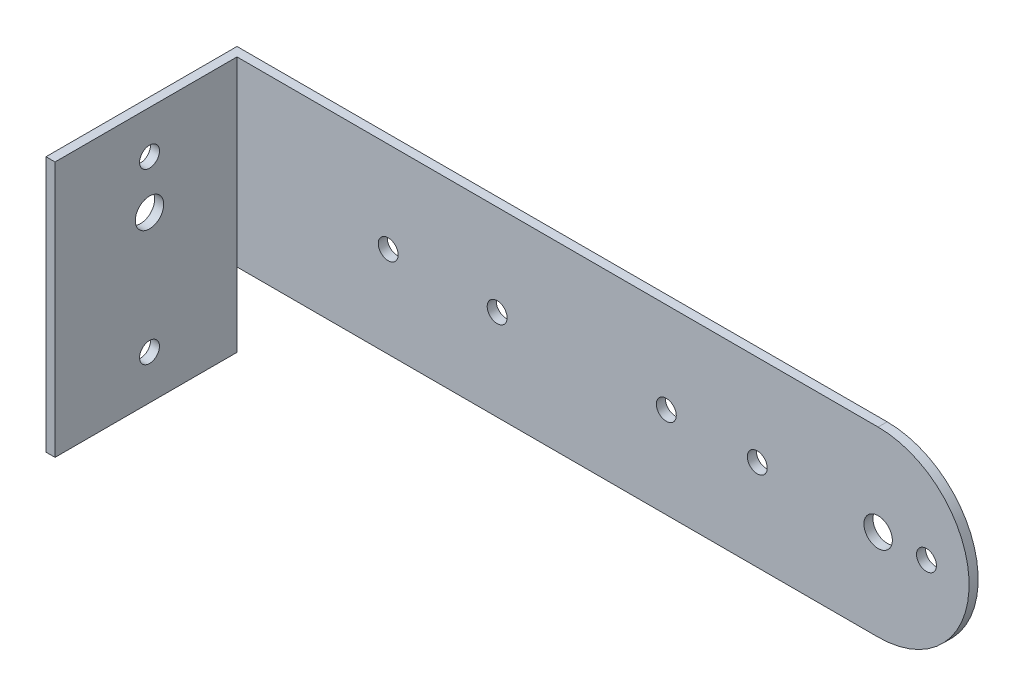
SolidWorks part; units mm, degrees
material "6061 Alloy"
ref_plane "Front Plane" through (0, 0, 0) normal (0, 0, 1) x (1, 0, 0)
ref_plane "Top Plane" through (0, 0, 0) normal (0, 1, 0) x (1, 0, 0)
ref_plane "Right Plane" through (0, 0, 0) normal (1, 0, 0) x (0, 0, -1)
sketch "Sketch1" plane through (0, 0, 0) normal (0, 0, 1) x (1, 0, 0)
  line L0 (0, 16) -> (-114.34, 16)
  line L1 (-114.34, 16) -> (-114.34, -16)
  line L2 (-114.34, -16) -> (0, -16)
  arc A0 (0, -16) -> (0, 16) centre (0, 0) ccw
  dimension "D1" = 16
  dimension "D2" = 114.34
extrude "Boss-Extrude1" add sketch "Sketch1" along normal blind 1.59
sketch "Sketch2" plane through (0, 0, 1.59) normal (0, 0, 1) x (1, 0, 0)
  line L1 (-114.34, 16) -> (-112.75, 16)
  line L2 (-114.34, 16) -> (-114.34, -29)
  line L3 (-114.34, -29) -> (-112.75, -29)
  line L4 (-112.75, 16) -> (-112.75, -29)
  point P5 (-112.75, -6.5)
  dimension "D1" = 45
  dimension "D2" = 1.59
extrude "Boss-Extrude2" add sketch "Sketch2" along normal blind 32
sketch "Sketch3" plane through (0, 0, 1.59) normal (0, 0, 1) x (1, 0, 0)
  line L0 (16, 0) -> (-148.456, 0) construction
  line L1 (-112.75, -16) -> (-112.75, 16) construction
  arc A0 (0, -16) -> (0, 16) centre (0, 0) ccw construction
  circle A1 centre (0, 0) radius 2.5
  circle A2 centre (8.5, 0) radius 1.75
  circle A3 centre (-21.25, 0) radius 1.75
  circle A4 centre (-37.25, 0) radius 1.75
  circle A5 centre (-67, 0) radius 1.75
  circle A6 centre (-86.16, 0) radius 1.75
  dimension "D5" = 3.5
  dimension "D6" = 5
  dimension "D7" = 26.59
  dimension "D1" = 29.75
  dimension "D2" = 16
  dimension "D3" = 8.5
  dimension "D4" = 29.75
extrude "Cut-Extrude1" cut sketch "Sketch3" against normal through all
sketch "Sketch4" plane through (-114.34, 0, 0) normal (-1, 0, 0) x (0, 0, 1)
  line L0 (16.975, 19.3535) -> (16.975, -38.9502) construction
  line L1 (0, 16) -> (0, -16) construction
  circle A0 centre (16.975, 0) radius 2.5
  circle A1 centre (16.975, 8.5) radius 1.75
  circle A2 centre (16.975, -21.25) radius 1.75
  dimension "D4" = 5
  dimension "D5" = 3.5
  dimension "D6" = 3.5
  dimension "D1" = 16.975
  dimension "D2" = 8.5
  dimension "D3" = 29.75
extrude "Cut-Extrude2" cut sketch "Sketch4" against normal through all
